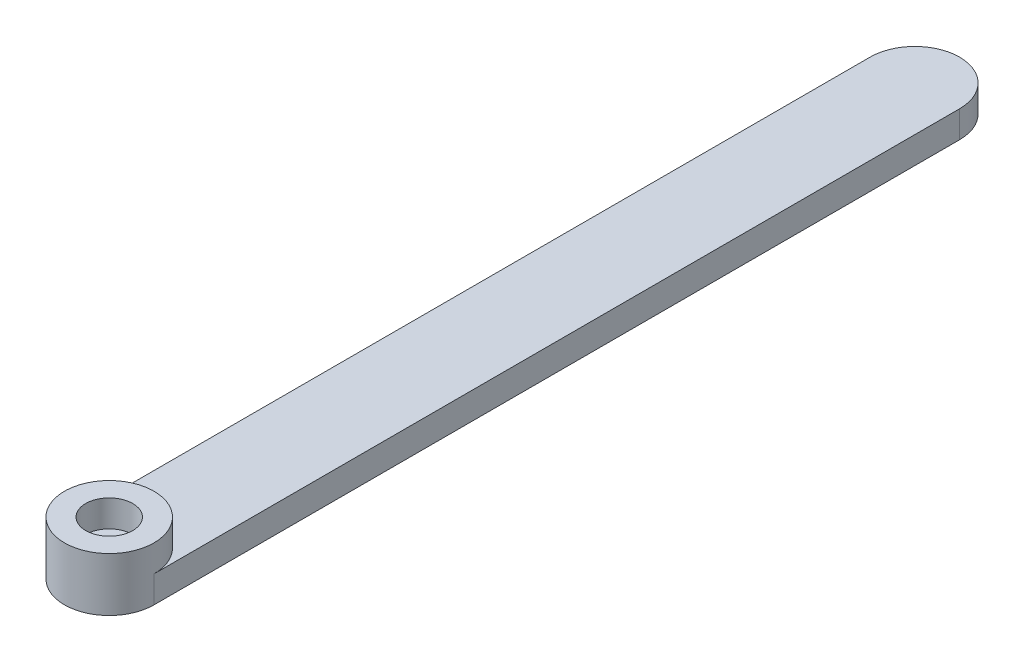
SolidWorks part; units mm, degrees
material "ABS"
ref_plane "Alzado" through (0, 0, 0) normal (0, 0, 1) x (1, 0, 0)
ref_plane "Planta" through (0, 0, 0) normal (0, 1, 0) x (1, 0, 0)
ref_plane "Vista lateral" through (0, 0, 0) normal (1, 0, 0) x (0, 0, -1)
sketch "Croquis1" plane through (0, 0, 0) normal (0, 1, 0) x (1, 0, 0)
  line L0 (0, 0) -> (0, 90) construction
  line L1 (-5, 0) -> (-5, 90)
  line L2 (5, 0) -> (5, 90)
  circle A1 centre (0, 0) radius 1.15
  arc A2 (-5, 0) -> (5, 0) centre (0, 0) ccw
  arc A3 (5, 90) -> (-5, 90) centre (0, 90) ccw
  point P1 (0, 45)
  dimension "D1" = 5
  dimension "D2" = 2.3
  dimension "D3" = 90
extrude "Saliente-Extruir1" add sketch "Croquis1" along normal blind 3
sketch "Croquis2" plane through (0, 3, 0) normal (0, 1, 0) x (1, 0, 0)
  circle A0 centre (0, 0) radius 5
  circle A1 centre (0, 0) radius 2.625
  dimension "D1" = 5.25
extrude "Saliente-Extruir2" add sketch "Croquis2" along normal blind 3
